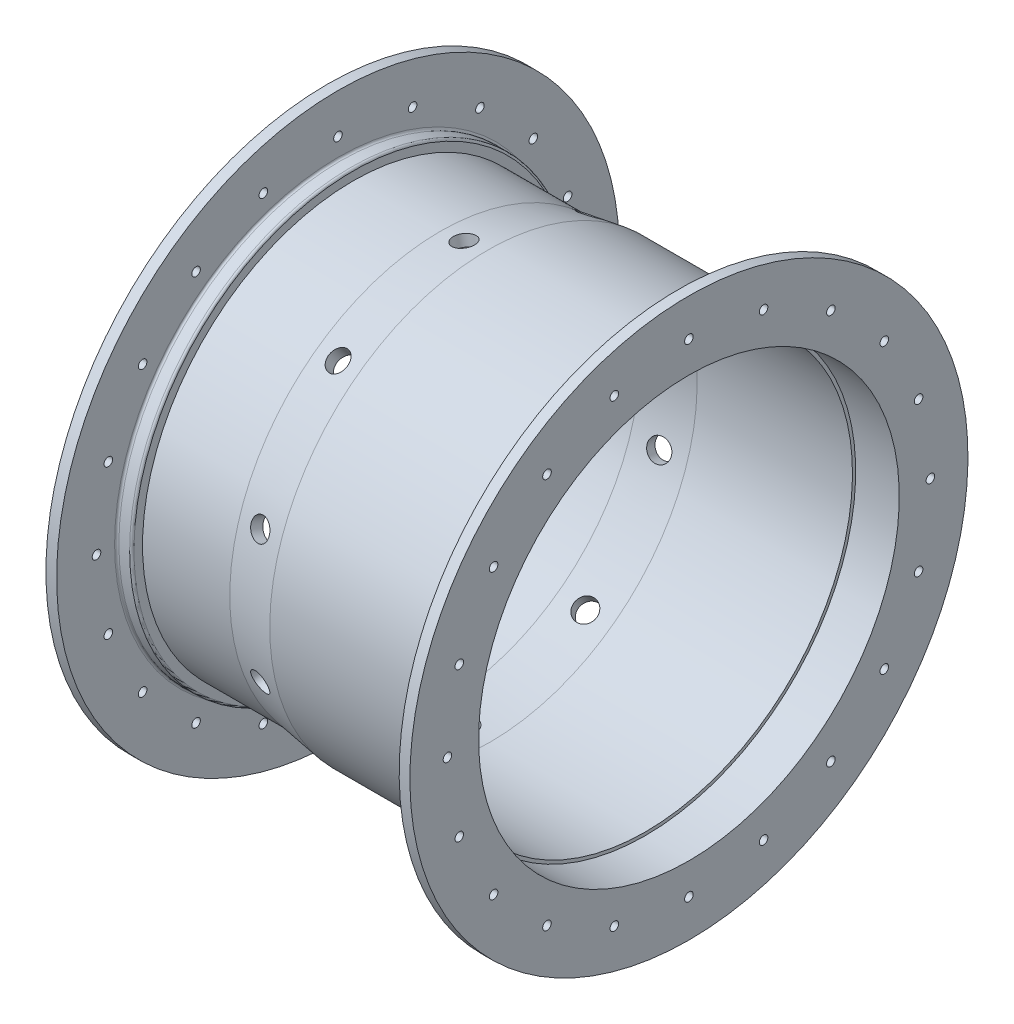
SolidWorks part; units mm, degrees
ref_plane "Front Plane" through (0, 0, 0) normal (0, 0, 1) x (1, 0, 0)
ref_plane "Top Plane" through (0, 0, 0) normal (0, 1, 0) x (1, 0, 0)
ref_plane "Right Plane" through (0, 0, 0) normal (1, 0, 0) x (0, 0, -1)
sketch "Sketch1" plane through (0, 0, 0) normal (0, 0, 1) x (1, 0, 0)
  line L0 (-85.258, 0) -> (85.258, 0) construction
  line L2 (84.25, 130) -> (84.25, 98)
  line L3 (84.25, 130) -> (79.25, 130)
  line L4 (79.25, 130) -> (79.25, 101.5)
  line L5 (63.95, 96.5) -> (-8.4412, 96.5)
  line L6 (63.95, 96.5) -> (63.95, 98)
  line L7 (63.95, 98) -> (84.25, 98)
  line L8 (79.25, 101.5) -> (-9.55, 101.5)
  line L9 (-9.55, 101.5) -> (-31.59, 98.0805)
  line L10 (-8.4412, 96.5) -> (-31.59, 92.9085)
  line L12 (-84.25, 131.0805) -> (-79.25, 131.0805)
  line L13 (-84.25, 131.0805) -> (-84.25, 98.0805)
  line L14 (-77.238, 98.0805) -> (-84.25, 98.0805)
  line L15 (-79.25, 131.0805) -> (-79.25, 103.0805)
  line L16 (-79.25, 103.0805) -> (-72.238, 103.0805)
  line L17 (-72.238, 103.0805) -> (-72.238, 98.0805)
  line L18 (-72.238, 98.0805) -> (-31.59, 98.0805)
  line L19 (-31.59, 92.9085) -> (-67.8252, 92.9085)
  line L20 (-67.8252, 92.9085) -> (-67.8252, 86.9085)
  line L21 (-77.238, 98.0805) -> (-77.238, 86.9085)
  line L22 (-77.238, 86.9085) -> (-67.8252, 86.9085)
  point P4 (0, 0)
  dimension "D1" = 22.04
  dimension "D2" = 73.5
  dimension "D3" = 5
  dimension "D4" = 1.5
  dimension "D5" = 20.3
  dimension "D6" = 33
  dimension "D7" = 6
  dimension "D8" = 84.25
  dimension "D9" = 168.5
  dimension "D10" = 130
  dimension "D11" = 101.5
  dimension "D12" = 5
revolve "Revolve1" add sketch "Sketch1" angle 360 about L0
sketch "Sketch2" plane through (0, 0, 0) normal (0, 0, 1) x (1, 0, 0)
  line L0 (-9.55, 101.5) -> (-31.59, 98.0805) construction
  line L1 (-9.55, 101.5) -> (-31.59, 98.0805) construction
  line L2 (-9.55, 101.5) -> (-9.55, 133.7693) construction
  line L3 (-20.57, 99.7903) -> (-25.5617, 128.0994) construction
  line L4 (-20.9353, 101.8618) -> (-25.8593, 100.9936)
  line L5 (-25.8593, 100.9936) -> (-24.2028, 91.5991)
  line L6 (-24.2028, 91.5991) -> (-19.2788, 92.4673)
  line L7 (-19.2788, 92.4673) -> (-20.9353, 101.8618)
  dimension "D1" = 10
  dimension "D2" = 5
  dimension "D3" = 2
revolve "Cut-Revolve1" cut sketch "Sketch2" angle 360 about L3
pattern_circular "CirPattern1" count 10 over 360 about axis through (-85.258, 0, 0) along (-1, 0, 0) of "Cut-Revolve1"
sketch "Sketch3" plane through (-84.25, 0, 0) normal (-1, 0, 0) x (0, 0, 1)
  circle A0 centre (0, 112.5) radius 2
  dimension "D1" = 4
  dimension "D2" = 112.5
extrude "Cut-Extrude1" cut sketch "Sketch3" against normal through all
pattern_circular "CirPattern2" count 20 over 360 about axis through (0, 0, 0) along (1, 0, 0) of "Cut-Extrude1"
fillet "Fillet1" radius 1 3 edges at (79.25, -101.5, 0) (-72.238, -103.0805, 0) (-79.25, -103.0805, 0)
